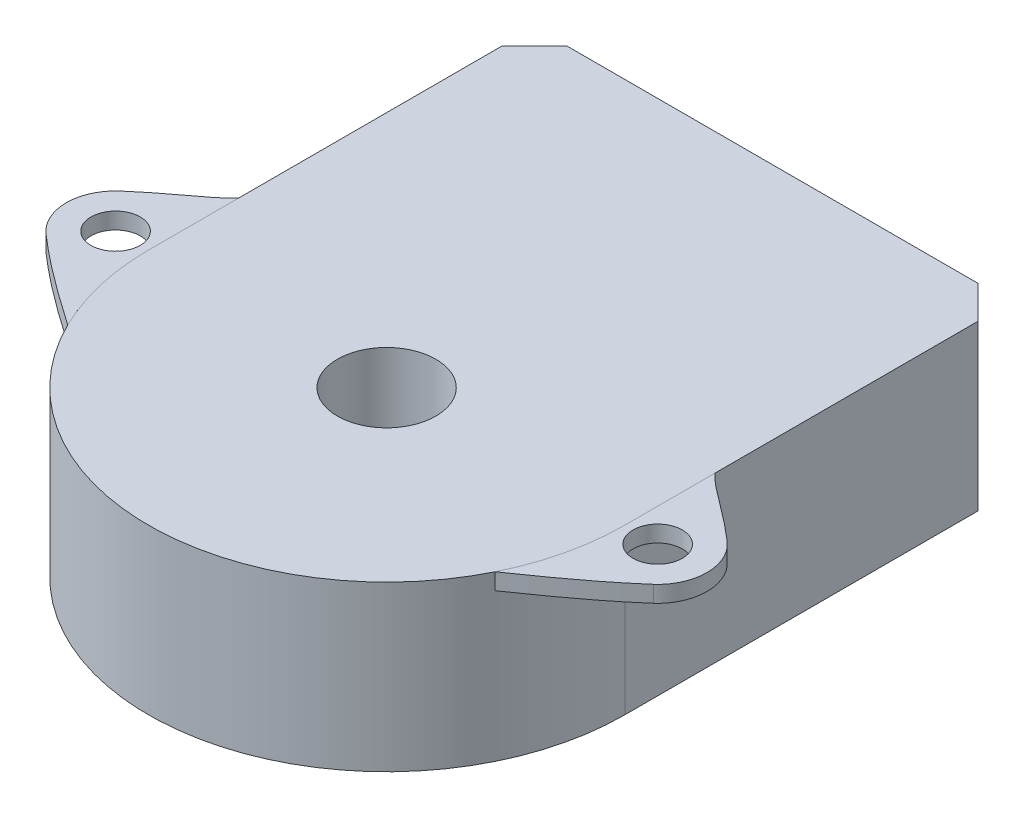
SolidWorks part; units mm, degrees
ref_plane "Alzado" through (0, 0, 0) normal (1, 0, 0) x (0, 1, 0)
ref_plane "Planta" through (0, 0, 0) normal (0, 0, 1) x (0, 1, 0)
ref_plane "Vista lateral" through (0, 0, 0) normal (0, 1, 0) x (-1, 0, 0)
sketch "Croquis1" plane through (0, 0, 0) normal (0, 1, 0) x (-1, 0, 0)
  line L0 (-14.5, 23.5) -> (-14.5, 0)
  line L1 (14.5, 23.5) -> (14.5, 0)
  line L2 (-14.5, 0) -> (14.5, 0)
  line L3 (0, 23.5) -> (0, 0) construction
  line L4 (0, 23.5) -> (0, 38) construction
  circle A0 centre (0, 23.5) radius 14.5
  circle A1 centre (0, 23.5) radius 3
  point P9 (0, 0)
  dimension "D3" = 6
  dimension "D1" = 29
  dimension "D2" = 38
extrude "Saliente-Extruir1" add sketch "Croquis1" along normal blind 10 contours A0 | A0 L0 L2 L1
sketch "Croquis2" plane through (0, 10, 0) normal (0, 1, 0) x (-1, 0, 0)
  line L0 (0, 23.5) -> (0, 0) construction
  line L1 (-14.5, 23.5) -> (-14.5, 0) construction
  line L2 (-14.5, 23.5) -> (-14.5, 18)
  line L3 (14.5, 23.5) -> (14.5, 18)
  line L4 (-19.5, 23.5) -> (19.5, 23.5) construction
  line L5 (0, 23.5) -> (-16.5, 23.5) construction
  circle A0 centre (-16.5, 23.5) radius 1.5
  arc A1 (14.5, 23.5) -> (-14.5, 23.5) centre (0, 23.5) ccw construction
  arc A2 (-18.4843, 25.75) -> (-18.4843, 21.25) centre (-16.5, 23.5) ccw
  circle A3 centre (16.5, 23.5) radius 1.5
  arc A4 (-13.0111, 29.9002) -> (-14.5, 23.5) centre (0, 23.5) ccw
  arc A5 (13.0111, 29.9002) -> (14.5, 23.5) centre (0, 23.5) cw
  arc A6 (18.4843, 25.75) -> (18.4843, 21.25) centre (16.5, 23.5) cw
  spline S0 degree 3 poles (-13.0111, 29.9002) (-14.9527, 28.5684) (-16.8993, 27.1478) (-18.4843, 25.75) knots 0 0 0 0 1 1 1 1
  spline S1 degree 3 poles (-14.5, 18) (-14.9515, 18.6273) (-16.8643, 19.8213) (-18.4843, 21.25) knots 0.453929 0.453929 0.453929 0.453929 1 1 1 1
  spline S2 degree 3 poles (13.0111, 29.9002) (14.9527, 28.5684) (16.8993, 27.1478) (18.4843, 25.75) knots 0 0 0 0 1 1 1 1
  spline S3 degree 3 poles (14.5, 18) (14.9515, 18.6273) (16.8643, 19.8213) (18.4843, 21.25) knots 0.453929 0.453929 0.453929 0.453929 1 1 1 1
  point P19 (18.5209, 25.7172)
  arc M11 (14.5, 23.5) -> (-14.5, 23.5) centre (0, 23.5) ccw
  line M12 (-14.5, 23.5) -> (-14.5, 0)
  line M14 (14.5, 0) -> (14.5, 23.5)
  dimension "D3" = 6
  dimension "D2" = 3
  dimension "D1" = 33
  dimension "D4" = 6.4002
  dimension "D5" = 5
  dimension "D6" = 2.25
  dimension "D7" = 15
  dimension "D8" = 2.25
  dimension "D9" = 5
  dimension "D10" = 15
  dimension "D11" = 5.5
  dimension "D12" = 39
extrude "Saliente-Extruir2" add sketch "Croquis2" against normal blind 1 separate body contours S1 S0 A2 A0 M12 M11 | S3 A6 S2 A3 M14 M11
chamfer "Chaflán1" distance 2 angle 45 2 edges at (-14.5, 5, 0) (14.5, 5, 0)
equation "\"ancho\"=29"
equation "\"D1@Croquis1\"=\"ancho\""
equation "\"altura\"=38"
equation "\"D2@Croquis1\"=\"altura\""
equation "\"esp\"=10"
equation "\"D1@Saliente-Extruir1\"=\"esp\""
equation "\"dist_agujeros\"=33"
equation "\"D1@Croquis2\"=\"dist_agujeros\""
equation "\"d_agujeros_suj\"=3"
equation "\"D2@Croquis2\"=\"d_agujeros_suj\""
equation "\"d_agujero_eje\"=6"
equation "\"D3@Croquis1\"=\"d_agujero_eje\""
